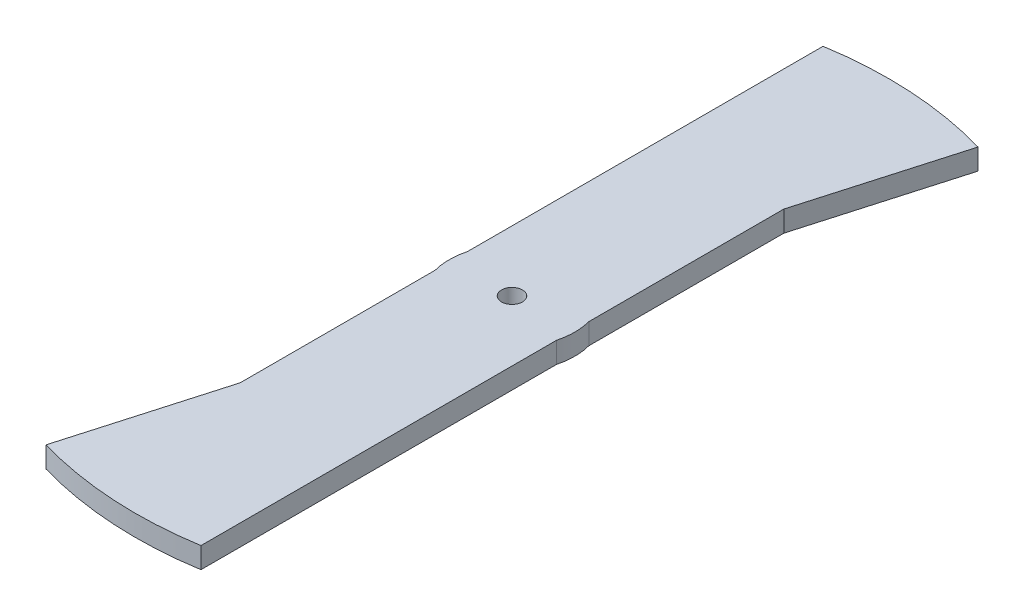
SolidWorks part; units mm, degrees
material "AISI 316 Stainless Steel Sheet (SS)"
ref_plane "Front Plane" through (0, 0, 0) normal (0, 0, 1) x (1, 0, 0)
ref_plane "Top Plane" through (0, 0, 0) normal (0, 1, 0) x (1, 0, 0)
ref_plane "Right Plane" through (0, 0, 0) normal (1, 0, 0) x (0, 0, -1)
sketch "Sketch1" plane through (0, 0, 0) normal (0, 1, 0) x (1, 0, 0)
  line L0 (0, 19.05) -> (0, 114.3) construction
  line L1 (-18.415, 112.8068) -> (-18.415, 4.8775)
  line L2 (18.415, 4.8775) -> (18.415, 64.0815)
  line L3 (18.415, 64.0815) -> (31.5686, 109.8541)
  line L4 (18.415, -112.8068) -> (18.415, -4.8775)
  line L5 (-18.415, -64.0815) -> (-31.5686, -109.8541)
  line L6 (-18.415, -4.8775) -> (-18.415, -64.0815)
  circle A0 centre (0, 0) radius 3.175
  circle A1 centre (0, 0) radius 19.05 construction
  circle A2 centre (0, 0) radius 114.3 construction
  arc A3 (-18.415, 112.8068) -> (31.5686, 109.8541) centre (0, 0) cw
  circle A4 centre (0, 0) radius 66.675 construction
  arc A5 (18.415, -112.8068) -> (-31.5686, -109.8541) centre (0, 0) cw
  arc A6 (-18.415, 4.8775) -> (-18.415, -4.8775) centre (0, 0) ccw
  arc A7 (18.415, 4.8775) -> (18.415, -4.8775) centre (0, 0) cw
  point P9 (18.415, 4.8775)
  point P15 (0, 66.675)
  point P23 (0, 0)
  dimension "D1" = 6.35
  dimension "D2" = 38.1
  dimension "D3" = 228.6
  dimension "D4" = 36.83
  dimension "D6" = 2
extrude "Boss-Extrude1" add sketch "Sketch1" along normal blind 6.35 contours A7 L2 L3 A3 L1 A6 L6 L5 A5 L4 A0
